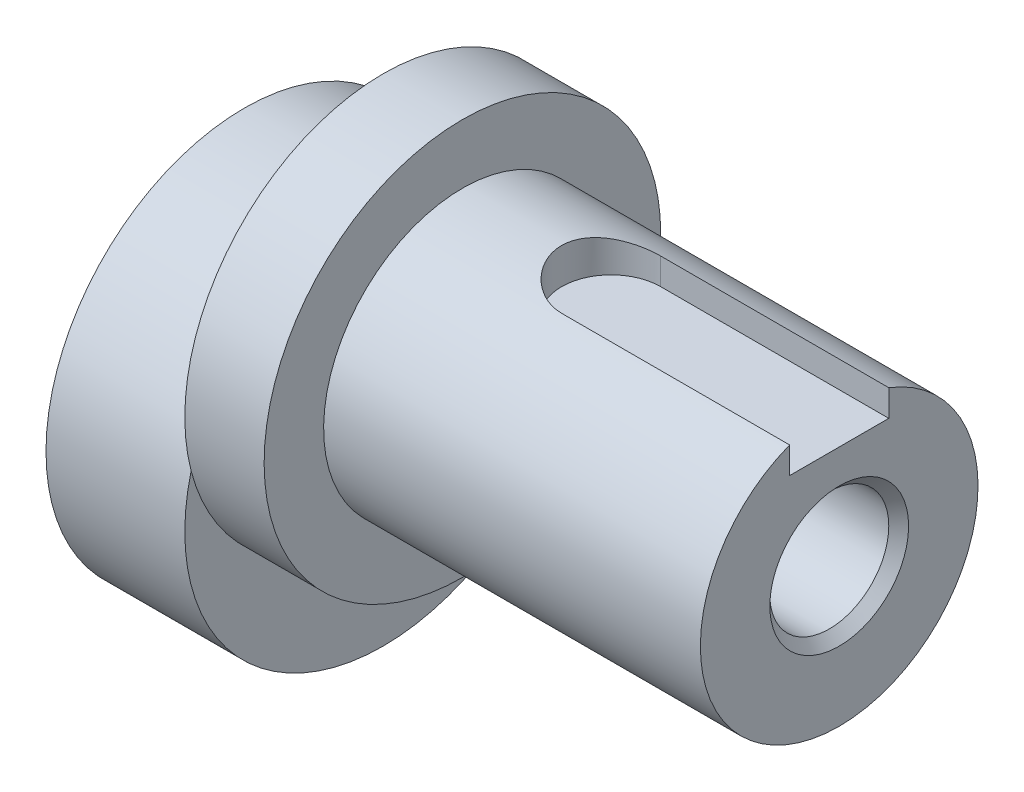
SolidWorks part; units mm, degrees
ref_plane "Front Plane" through (0, 0, 0) normal (0, 0, 1) x (1, 0, 0)
ref_plane "Top Plane" through (0, 0, 0) normal (0, 1, 0) x (1, 0, 0)
ref_plane "Right Plane" through (0, 0, 0) normal (1, 0, 0) x (0, 0, -1)
sketch "Sketch1" plane through (0, 0, 0) normal (1, 0, 0) x (0, 0, -1)
  circle A0 centre (0, 0) radius 10
  dimension "D1" = 20
extrude "Boss-Extrude1" add sketch "Sketch1" along normal blind 7
sketch "Sketch2" plane through (7, 0, 0) normal (1, 0, 0) x (0, 0, -1)
  circle A0 centre (0, 5) radius 10
  dimension "D1" = 20
  dimension "D2" = 5
extrude "Boss-Extrude2" add sketch "Sketch2" along normal blind 4
sketch "Sketch3" plane through (11, 0, 0) normal (1, 0, 0) x (0, 0, -1)
  circle A0 centre (0, 5) radius 7
  dimension "D1" = 14
extrude "Boss-Extrude3" add sketch "Sketch3" along normal blind 19
sketch "Sketch4" plane through (30, 0, 0) normal (1, 0, 0) x (0, 0, -1)
  circle A0 centre (0, 5) radius 3
  dimension "D1" = 6
extrude "Cut-Extrude1" cut sketch "Sketch4" against normal through all
chamfer "Chamfer1" distance 0.5 angle 45 2 edges at (0, 5, -3) (30, 5, -3)
sketch "Sketch5" plane through (0, 0, 0) normal (0, 1, 0) x (1, 0, 0)
  line L3 (30, -2.5) -> (18.5, -2.5)
  line L5 (30, 2.5) -> (18.5, 2.5)
  line L7 (30, -2.5) -> (18.5, 2.5) construction
  line L8 (30, 2.5) -> (18.5, -2.5) construction
  line L9 (30, 2.5) -> (31, 2.5)
  line L11 (30, -2.5) -> (31, -2.5)
  line L12 (31, 2.5) -> (31, -2.5)
  arc A0 (18.5, 2.5) -> (18.5, -2.5) centre (18.5, 0) ccw
  point P5 (24.25, 0)
  dimension "D2" = 2.5
  dimension "D3" = 1
extrude "Cut-Extrude2" cut sketch "Sketch5" along normal through all from offset 10.2
